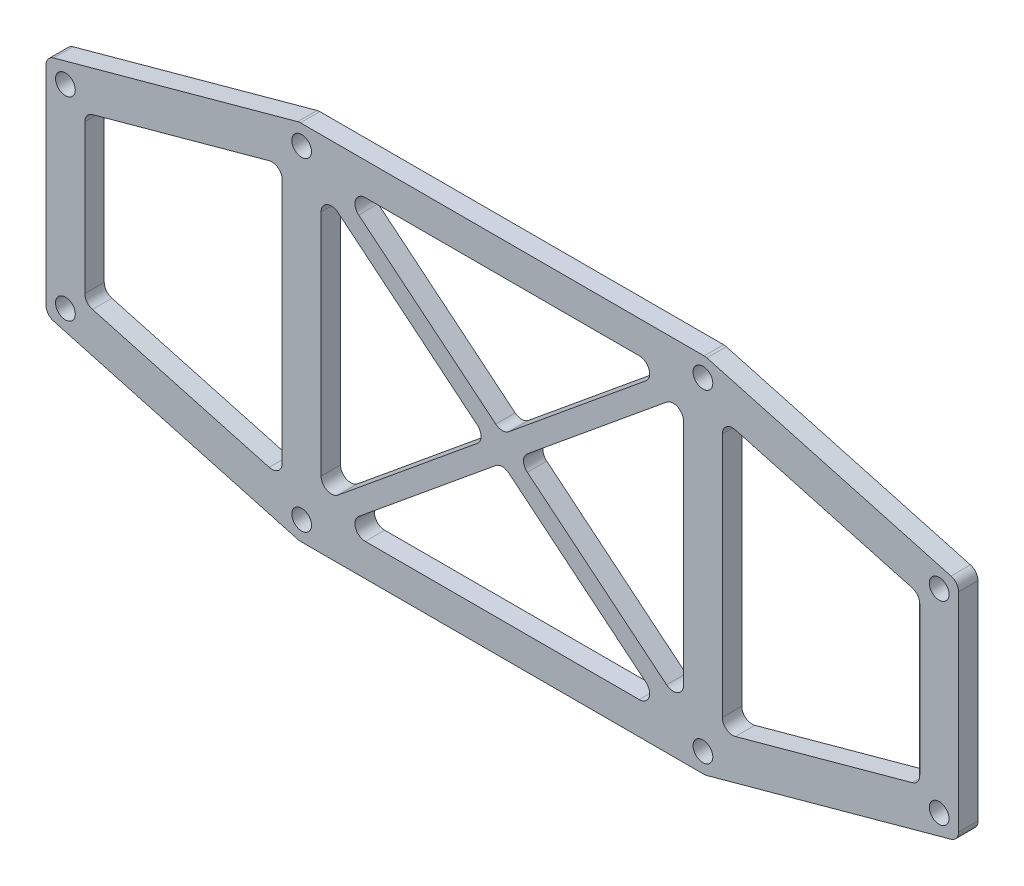
SolidWorks part; units mm, degrees
material "A-玻璃纤维"
ref_plane "前视基准面" through (0, 0, 0) normal (0, 0, 1) x (1, 0, 0)
ref_plane "上视基准面" through (0, 0, 0) normal (0, 1, 0) x (1, 0, 0)
ref_plane "右视基准面" through (0, 0, 0) normal (1, 0, 0) x (0, 0, -1)
other "Configuration Table"
sketch "草图1" plane through (0, 0, 0) normal (0, 0, 1) x (1, 0, 0)
  line L0 (-67.5, 0) -> (67.5, 0) construction
  line L1 (-31, -25) -> (31, -25) construction
  line L2 (-31, -25) -> (-31, 25) construction
  line L3 (-31, 25) -> (31, 25) construction
  line L4 (31, -25) -> (31, 25) construction
  line L5 (-31, -25) -> (31, 25) construction
  line L6 (-31, 25) -> (31, -25) construction
  line L7 (67.5, 15) -> (67.5, -15) construction
  line L8 (-67.5, 15) -> (-67.5, -15) construction
  line L9 (-70.5, 17.2886) -> (-31.4035, 28)
  line L10 (-31.4035, 28) -> (31.4035, 28)
  line L11 (31.4035, 28) -> (70.5, 17.2886)
  line L12 (70.5, 17.2886) -> (70.5, -17.2886)
  line L13 (-70.5, 17.2886) -> (-70.5, -17.2886)
  line L14 (-67.5, 15) -> (-31, 25) construction
  line L15 (31, 25) -> (67.5, 15) construction
  line L16 (-70.5, -17.2886) -> (-31.4035, -28)
  line L17 (-31.4035, -28) -> (31.4035, -28)
  line L18 (31.4035, -28) -> (70.5, -17.2886)
  circle A0 centre (31, 25) radius 1.525
  circle A1 centre (-31, 25) radius 1.525
  circle A2 centre (-31, -25) radius 1.525
  circle A3 centre (31, -25) radius 1.525
  circle A4 centre (-67.5, -15) radius 1.525
  circle A5 centre (-67.5, 15) radius 1.525
  circle A6 centre (67.5, 15) radius 1.525
  circle A7 centre (67.5, -15) radius 1.525
  point P0 (0, 0)
  point P13 (0, 0)
  point P16 (67.5, 0)
  point P19 (-67.5, 0)
  point P30 (-70.5, 0)
  point P33 (70.5, 0)
  dimension "D3" = 3.05
  dimension "D6" = 3.05
  dimension "D1" = 62
  dimension "D2" = 50
  dimension "D4" = 135
  dimension "D5" = 30
  dimension "D7" = 3
  dimension "D8" = 3
  dimension "D9" = 3
  dimension "D10" = 3
  dimension "D11" = 3
extrude "凸台-拉伸1" add sketch "草图1" along normal blind 3
sketch "草图2" plane through (0, 0, 3) normal (0, 0, 1) x (1, 0, 0)
  line L0 (31.4035, 28) -> (-31.4035, 28) construction
  line L1 (-28, -23) -> (28, -23)
  line L2 (-28, -23) -> (-28, 23)
  line L3 (-28, 23) -> (28, 23)
  line L4 (28, -23) -> (28, 23)
  line L5 (-28, -23) -> (28, 23) construction
  line L6 (-28, 23) -> (28, -23) construction
  line L7 (-28.9521, 21.8409) -> (27.0479, -24.1591)
  line L8 (-27.0479, -24.1591) -> (28.9521, 21.8409)
  line L9 (-27.0479, 24.1591) -> (28.9521, -21.8409)
  line L10 (-28.9521, -21.8409) -> (27.0479, 24.1591)
  circle A0 centre (31, 25) radius 1.525 construction
  point P0 (0, 0)
  dimension "D1" = 5
  dimension "D2" = 3
  dimension "D3" = 1.5
  dimension "D4" = 1.5
extrude "切除-拉伸1" cut sketch "草图2" against normal blind 3 contours L2 L10 L7 | L8 L1 L7 | L8 L9 L4 | L9 L10 L3
sketch "草图3" plane through (0, 0, 3) normal (0, 0, 1) x (1, 0, 0)
  line L0 (31, 25) -> (31, -25) construction
  line L1 (31, -25) -> (67.5, -15) construction
  line L2 (67.5, -15) -> (67.5, 15) construction
  line L3 (67.5, 15) -> (31, 25) construction
  line L4 (34, 21.0675) -> (34, -21.0675)
  line L5 (34, -21.0675) -> (64.5, -12.7114)
  line L6 (64.5, -12.7114) -> (64.5, 12.7114)
  line L7 (64.5, 12.7114) -> (34, 21.0675)
  line L8 (0, 0) -> (0, 28) construction
  line L9 (31.4035, 28) -> (-31.4035, 28) construction
  line L10 (-64.5, 12.7114) -> (-34, 21.0675)
  line L11 (-64.5, -12.7114) -> (-64.5, 12.7114)
  line L12 (-34, -21.0675) -> (-64.5, -12.7114)
  line L13 (-34, 21.0675) -> (-34, -21.0675)
  dimension "D1" = 3
extrude "切除-拉伸2" cut sketch "草图3" against normal blind 3
fillet "圆角1" radius 1.6 28 edges at (28, -21.0588, 1.5) (28, 21.0588, 1.5) (2.3632, 0, 1.5) (25.6368, -23, 1.5) (0, -1.9412, 1.5) (-25.6368, -23, 1.5) (-2.3632, 0, 1.5) (-28, 21.0588, 1.5) (-28, -21.0588, 1.5) (-70.5, 17.2886, 1.5) (-31.4035, 28, 1.5) (70.5, 17.2886, 1.5) (70.5, -17.2886, 1.5) (31.4035, -28, 1.5) (-31.4035, -28, 1.5) (-70.5, -17.2886, 1.5) (0, 1.9412, 1.5) (25.6368, 23, 1.5) (-25.6368, 23, 1.5) (-34, 21.0675, 1.5) (-64.5, 12.7114, 1.5) (-64.5, -12.7114, 1.5) (-34, -21.0675, 1.5) (31.4035, 28, 1.5) (34, 21.0675, 1.5) (64.5, 12.7114, 1.5) (64.5, -12.7114, 1.5) (34, -21.0675, 1.5)
